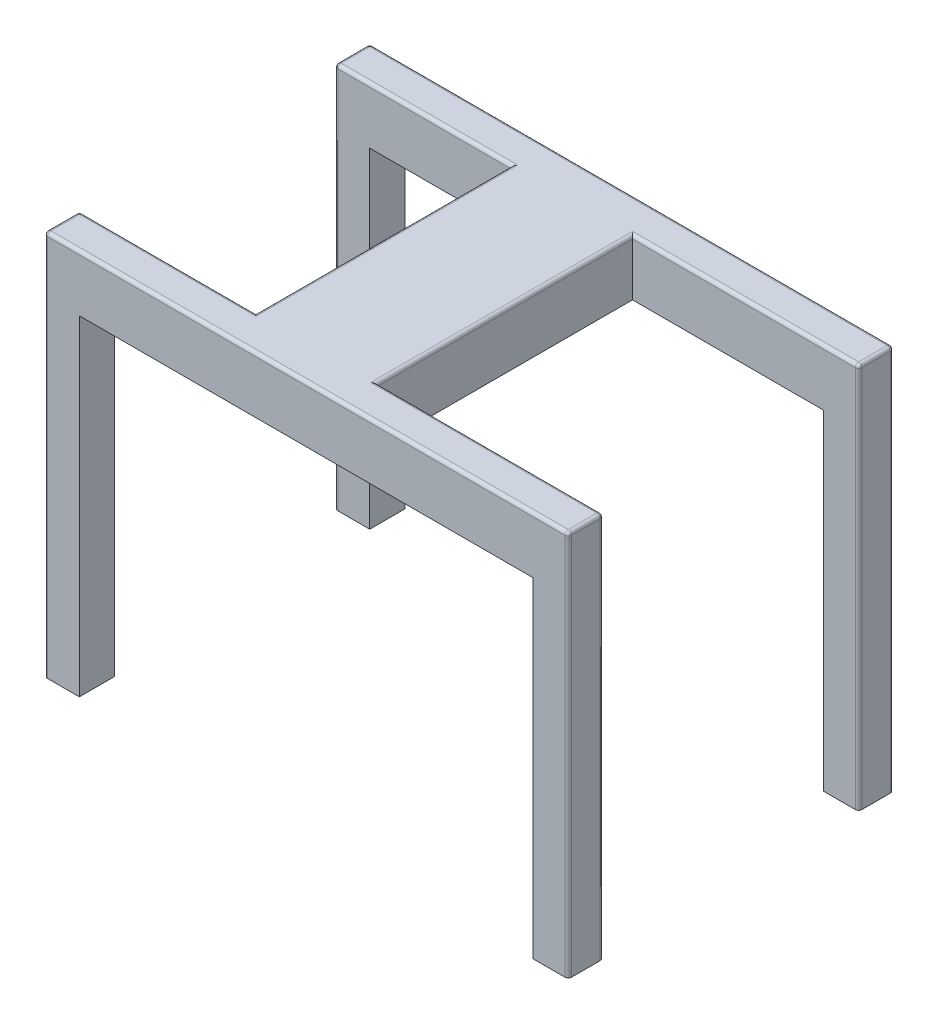
SolidWorks part; units mm, degrees
ref_plane "Alzado" through (0, 0, 0) normal (0, 0, 1) x (1, 0, 0)
ref_plane "Planta" through (0, 0, 0) normal (0, 1, 0) x (1, 0, 0)
ref_plane "Vista lateral" through (0, 0, 0) normal (1, 0, 0) x (0, 0, -1)
sketch "Croquis1" plane through (0, 0, 0) normal (0, 0, 1) x (1, 0, 0)
  line L1 (0, 0) -> (950, 0)
  line L2 (0, 0) -> (0, -700)
  line L3 (0, -700) -> (950, -700)
  line L4 (950, 0) -> (950, -700)
  dimension "D1" = 700
  dimension "D2" = 950
extrude "Saliente-Extruir1" add sketch "Croquis1" along normal blind 590
sketch "Croquis2" plane through (0, 0, 590) normal (0, 0, 1) x (1, 0, 0)
  line L0 (0, -700) -> (950, -700) construction
  line L1 (63.5, -700) -> (886.5, -700)
  line L2 (63.5, -700) -> (63.5, -101.6)
  line L3 (63.5, -101.6) -> (886.5, -101.6)
  line L4 (886.5, -700) -> (886.5, -101.6)
  line L5 (0, 0) -> (0, -700) construction
  line L6 (950, -700) -> (950, 0) construction
  line L7 (950, 0) -> (0, 0) construction
  dimension "D1" = 63.5
  dimension "D2" = 63.5
  dimension "D3" = 101.6
extrude "Cortar-Extruir1" cut sketch "Croquis2" against normal blind 1000
sketch "Croquis3" plane through (950, 0, 0) normal (1, 0, 0) x (0, 0, -1)
  line L0 (0, -101.6) -> (-590, -101.6) construction
  line L1 (-526.5, -101.6) -> (-63.5, -101.6)
  line L2 (-526.5, -101.6) -> (-526.5, -700)
  line L3 (-526.5, -700) -> (-63.5, -700)
  line L4 (-63.5, -101.6) -> (-63.5, -700)
  line L5 (-590, -700) -> (0, -700) construction
  line L6 (-590, -700) -> (-590, 0) construction
  line L7 (0, -700) -> (0, 0) construction
  dimension "D1" = 63.5
  dimension "D2" = 63.5
extrude "Cortar-Extruir2" cut sketch "Croquis3" against normal blind 1000
sketch "Croquis4" plane through (0, 0, 0) normal (0, 1, 0) x (1, 0, 0)
  line L0 (475, 0) -> (475, -590) construction
  line L1 (0, -63.5) -> (320, -63.5)
  line L2 (0, -63.5) -> (0, -526.5)
  line L3 (0, -526.5) -> (320, -526.5)
  line L4 (320, -63.5) -> (320, -526.5)
  line L5 (950, 0) -> (0, 0) construction
  line L6 (950, -590) -> (0, -590) construction
  line L8 (950, -63.5) -> (540, -63.5)
  line L9 (950, -63.5) -> (950, -526.5)
  line L10 (950, -526.5) -> (540, -526.5)
  line L11 (540, -63.5) -> (540, -526.5)
  dimension "D1" = 320
  dimension "D2" = 410
  dimension "D3" = 63.5
  dimension "D4" = 63.5
extrude "Cortar-Extruir3" cut sketch "Croquis4" against normal blind 200
fillet "Redondeo1" radius 6 4 edges at (0, 0, 31.75) (950, 0, 31.75) (950, 0, 558.25) (0, 0, 558.25)
fillet "Redondeo2" radius 6 2 edges at (540, 0, 295) (320, 0, 295)
fillet "Redondeo3" radius 6 22 edges at (950, -353, 590) (948.2426, -1.7574, 590) (0, -353, 590) (1.7574, -1.7574, 590) (950, -353, 0) (948.2426, -1.7574, 0) (0, -353, 0) (1.7574, -1.7574, 0) (950, -353, 526.5) (948.2426, -1.7574, 526.5) (0, -353, 526.5) (1.7574, -1.7574, 526.5) (0, -353, 63.5) (1.7574, -1.7574, 63.5) (950, -353, 63.5) (948.2426, -1.7574, 63.5) (475, 0, 590) (475, 0, 0) (739, 0, 526.5) (166, 0, 526.5) (166, 0, 63.5) (739, 0, 63.5)
